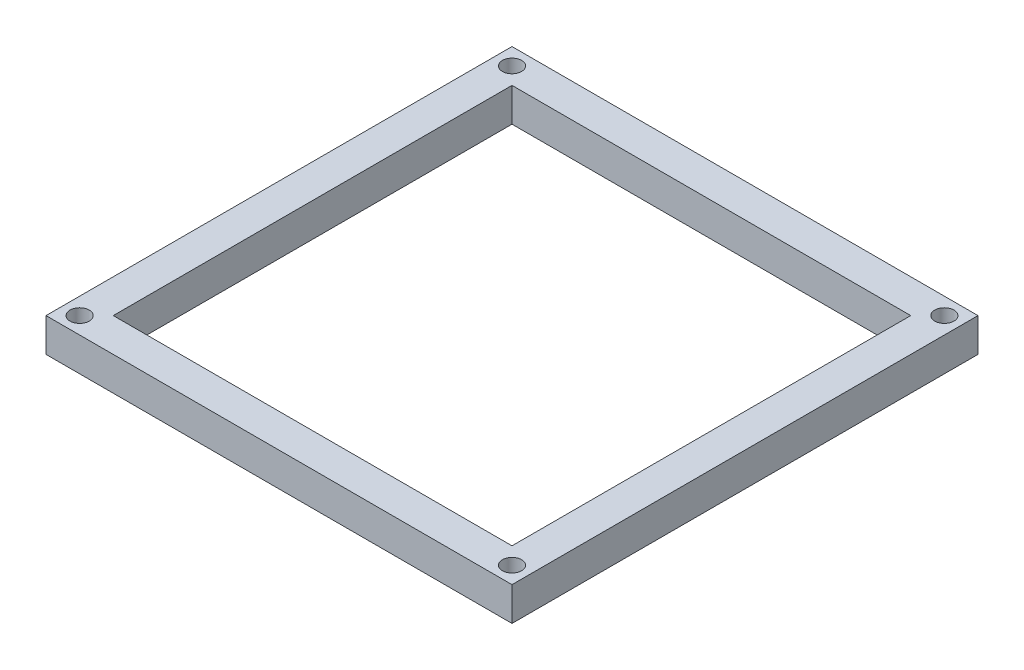
SolidWorks part; units mm, degrees
ref_plane "Front" through (0, 0, 0) normal (0, 0, 1) x (1, 0, 0)
ref_plane "Top" through (0, 0, 0) normal (0, 1, 0) x (1, 0, 0)
ref_plane "Right" through (0, 0, 0) normal (1, 0, 0) x (0, 0, -1)
sketch "Sketch1" plane through (0, 0, 0) normal (0, 1, 0) x (1, 0, 0)
  line L1 (0, 0) -> (97, 0)
  line L2 (0, 0) -> (0, 97)
  line L3 (0, 97) -> (97, 97)
  line L4 (97, 0) -> (97, 97)
  dimension "D1" = 97
  dimension "D2" = 97
extrude "Boss-Extrude1" add sketch "Sketch1" along normal blind 7
sketch "Sketch2" plane through (0, 7, 0) normal (0, 1, 0) x (1, 0, 0)
  line L0 (97, 97) -> (0, 97) construction
  line L1 (97, 0) -> (97, 97) construction
  line L3 (7, 7) -> (90, 7)
  line L4 (7, 7) -> (7, 90)
  line L5 (7, 90) -> (90, 90)
  line L6 (90, 7) -> (90, 90)
  line L7 (7, 7) -> (90, 90) construction
  line L8 (7, 90) -> (90, 7) construction
  point P0 (48.5, 97)
  point P1 (97, 48.5)
  point P4 (48.5, 48.5)
  dimension "D1" = 83
  dimension "D2" = 83
extrude "Cut-Extrude1" cut sketch "Sketch2" against normal blind 7
sketch "Sketch3" plane through (0, 7, 0) normal (0, 1, 0) x (1, 0, 0)
  line L1 (0, 97) -> (7, 97)
  line L2 (0, 97) -> (0, 90)
  line L3 (0, 90) -> (7, 90)
  line L4 (7, 97) -> (7, 90)
  line L5 (97, 0) -> (90, 0)
  line L6 (97, 0) -> (97, 7)
  line L7 (97, 7) -> (90, 7)
  line L8 (90, 0) -> (90, 7)
  circle A0 centre (3.5, 93.5) radius 2
  circle A1 centre (93.5, 3.5) radius 2
  circle A2 centre (3.5, 3.5) radius 2
  circle A3 centre (93.5, 93.5) radius 2
  point P12 (3.5, 97)
  point P13 (7, 93.5)
  point P14 (93.5, 7)
  point P15 (90, 3.5)
  dimension "D1" = 4
  dimension "D2" = 4
extrude "Cut-Extrude2" cut sketch "Sketch3" against normal blind 10 contours A0 | A3 | A2 | A1
